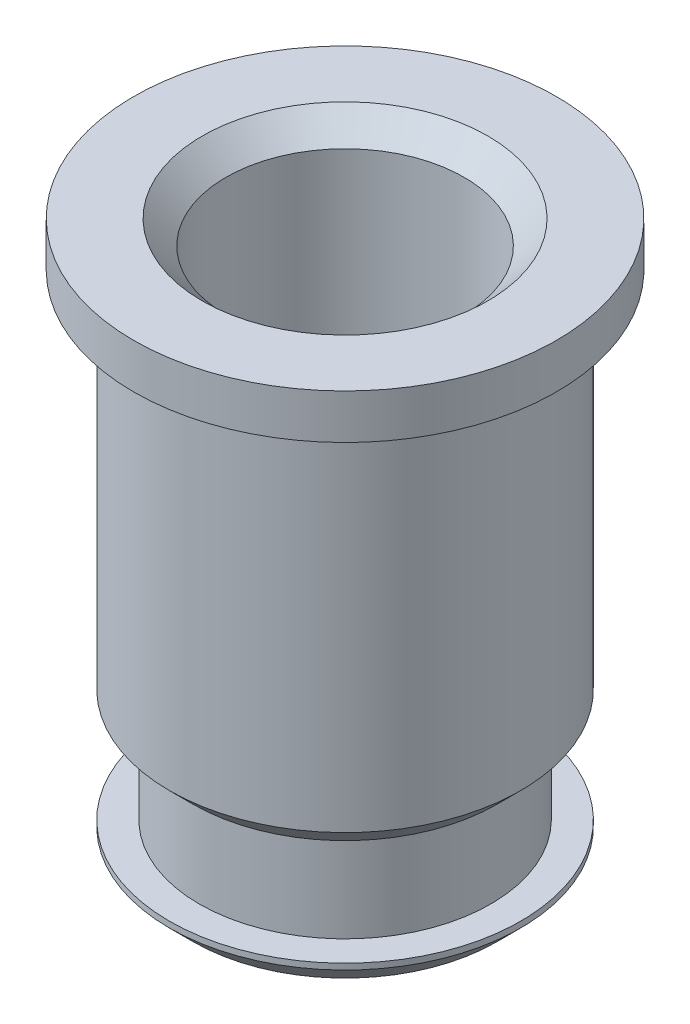
SolidWorks part; units mm, degrees
material "铸造碳钢"
ref_plane "前视基准面" through (0, 0, 0) normal (0, 0, 1) x (1, 0, 0)
ref_plane "上视基准面" through (0, 0, 0) normal (0, 1, 0) x (1, 0, 0)
ref_plane "右视基准面" through (0, 0, 0) normal (1, 0, 0) x (0, 0, -1)
sketch "草图1" plane through (0, 0, 0) normal (0, 1, 0) x (1, 0, 0)
  circle A0 centre (0, 0) radius 2
  circle A1 centre (0, 0) radius 2.95
  dimension "内径" = 4
  dimension "外径" = 5.9
extrude "凸台-拉伸1" add sketch "草图1" against normal blind 8.5
sketch "草图2" plane through (0, 0, 0) normal (0, 1, 0) x (1, 0, 0)
  circle A0 centre (0, 0) radius 2
  circle A1 centre (0, 0) radius 3.55
  circle A2 centre (0, 0) radius 2 construction
  dimension "翻边外径" = 7.1
extrude "凸台-拉伸2" add sketch "草图2" along normal blind 0.75
sketch "草图3" plane through (0, 0, 0) normal (1, 0, 0) x (0, 0, -1)
  line L0 (0, 0) -> (0, -8.5) construction
  line L1 (-2.95, -8.5) -> (2.95, -8.5) construction
  line L2 (-2.95, 0) -> (-2.95, -8.5) construction
  line L3 (-2.95, -6.5) -> (-2.45, -6.5)
  line L4 (-2.95, -6.5) -> (-2.95, -8)
  line L5 (-2.95, -8) -> (-2.45, -8)
  line L6 (-2.45, -6.5) -> (-2.45, -8)
  dimension "D1" = 0.5
  dimension "D2" = 1.5
  dimension "D3" = 0.5
revolve "切除-旋转1" cut sketch "草图3" angle 360 about L0
chamfer "倒角1" distance 0.4 angle 45 3 edges at (0, -6.5, 2.95) (0, -8.5, 2.95) (0, 0.75, 2)
other "冻结***"
